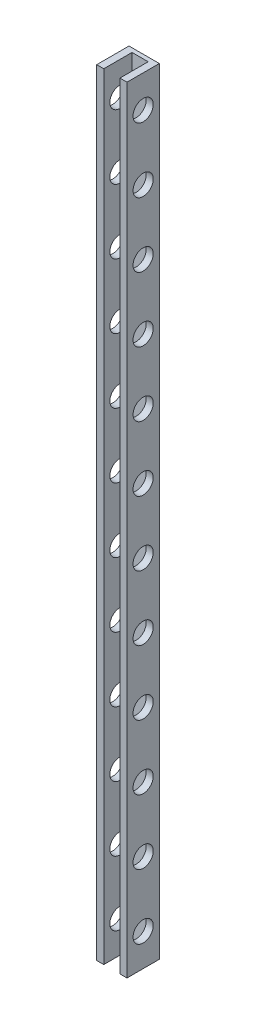
SolidWorks part; units mm, degrees
ref_plane "Plan de face" through (0, 0, 0) normal (0, 0, 1) x (1, 0, 0)
ref_plane "Plan de dessus" through (0, 0, 0) normal (0, 1, 0) x (1, 0, 0)
ref_plane "Plan de droite" through (0, 0, 0) normal (1, 0, 0) x (0, 0, -1)
sketch "Esquisse1" plane through (0, 0, 0) normal (0, 1, 0) x (1, 0, 0)
  line L0 (-2, -4) -> (-2, 3)
  line L1 (3.75, 4) -> (-3.75, 4)
  line L2 (3.75, 4) -> (3.75, -4)
  line L3 (3.75, -4) -> (2, -4)
  line L4 (-3.75, 4) -> (-3.75, -4)
  line L5 (3.75, 4) -> (-3.75, -4) construction
  line L6 (3.75, -4) -> (-3.75, 4) construction
  line L7 (-2, 3) -> (2, 3)
  line L8 (2, 3) -> (2, -4)
  line L9 (-2, 3) -> (2, -4) construction
  line L10 (0, -1.2247) -> (0, 2.1498) construction
  line L11 (-2, -4) -> (-3.75, -4)
  point P0 (0, 0)
  point P8 (0, -0.5)
  dimension "D1" = 7.5
  dimension "D2" = 8
  dimension "D3" = 1
  dimension "D4" = 4
extrude "Base" add sketch "Esquisse1" against normal blind 192
sketch "Esquisse2" plane through (-3.75, 0, 0) normal (-1, 0, 0) x (0, 0, 1)
  line L0 (0, 0) -> (0, -192) construction
  line L1 (-4, -192) -> (4, -192) construction
  line L3 (0, -5.5) -> (3.0778, -5.5) construction
  line L4 (-4, 0) -> (4, 0) construction
  circle A0 centre (0, -8) radius 2.5
  circle A1 centre (0, -24) radius 2.5
  circle A2 centre (0, -40) radius 2.5
  circle A3 centre (0, -56) radius 2.5
  circle A4 centre (0, -72) radius 2.5
  circle A5 centre (0, -88) radius 2.5
  circle A6 centre (0, -104) radius 2.5
  circle A7 centre (0, -120) radius 2.5
  circle A8 centre (0, -136) radius 2.5
  circle A9 centre (0, -152) radius 2.5
  circle A10 centre (0, -168) radius 2.5
  circle A11 centre (0, -184) radius 2.5
  dimension "D1" = 5
  dimension "D2" = 5.5
  dimension "D3" = 12
extrude "Trou" cut sketch "Esquisse2" against normal through all
